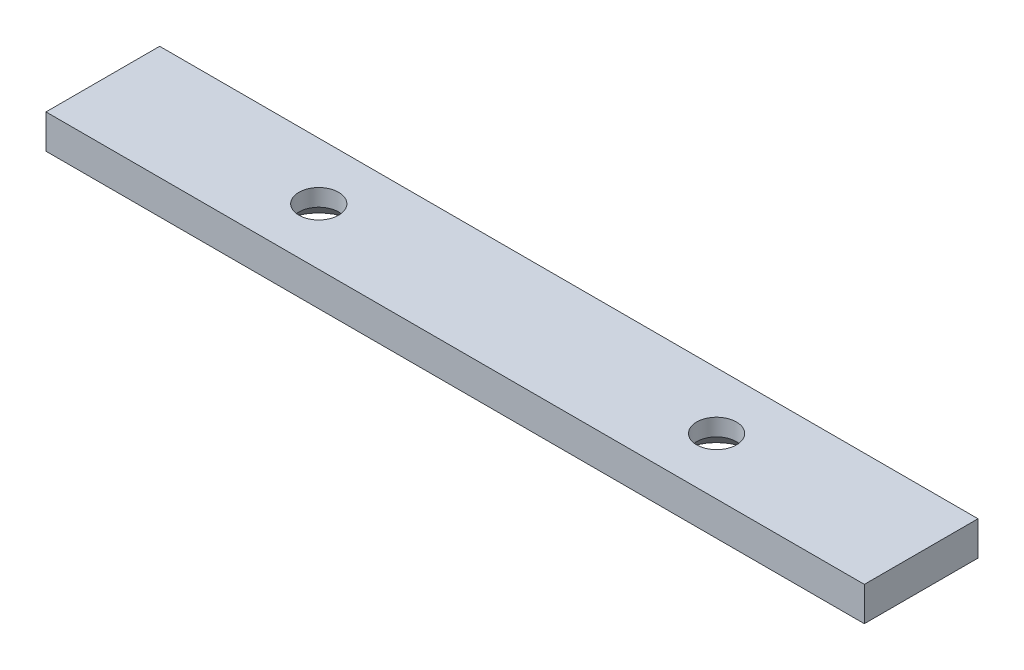
SolidWorks part; units mm, degrees
material "AISI 1020"
ref_plane "Front Plane" through (0, 0, 0) normal (0, 0, 1) x (1, 0, 0)
ref_plane "Top Plane" through (0, 0, 0) normal (0, 1, 0) x (1, 0, 0)
ref_plane "Right Plane" through (0, 0, 0) normal (1, 0, 0) x (0, 0, -1)
sketch "Sketch1" plane through (0, 0, 0) normal (0, 1, 0) x (1, 0, 0)
  line L1 (-72, 10) -> (72, 10)
  line L2 (-72, 10) -> (-72, -10)
  line L3 (-72, -10) -> (72, -10)
  line L4 (72, 10) -> (72, -10)
  line L5 (-72, 10) -> (72, -10) construction
  line L6 (-72, -10) -> (72, 10) construction
  point P0 (0, 0)
  dimension "D1" = 20
  dimension "D2" = 144
extrude "Boss-Extrude1" add sketch "Sketch1" along normal blind 6 contours L3 L4 L1 L2
hole_wizard "CSK for M2 Flat Head Machine Screw1" positions "Sketch4" profile "Sketch5" countersink size "M2" standard "ANSI Metric" end condition up to next
sketch "Sketch4" plane through (0, 0, 0) normal (0, -1, 0) x (-1, 0, 0)
  line L0 (72, 10) -> (72, -10) construction
  line L1 (72, 10) -> (-72, 10) construction
  point P0 (34, 0)
  dimension "D1" = 38
  dimension "D2" = 10
sketch "Sketch5" plane through (-34, 0, 0) normal (1, 0, 0) x (0, 0, -1)
  line L0 (0, 0) -> (0, 6)
  line L1 (0, 6) -> (3.5, 6)
  line L2 (3.5, 6) -> (3.5, 3)
  line L3 (3.5, 3) -> (6.5, 0)
  line L5 (6.5, 0) -> (0, 0)
  line L6 (-3.5, 3) -> (-6.5, 0) construction
  line L11 (0, -6.35) -> (0, 107.95) construction
  dimension "Thru Hole Dia." = 7
  dimension "Thru Hole Depth" = 6
  dimension "Near C'Sink Dia." = 13
  dimension "Near C'Sink Angle" = 90
pattern_linear "LPattern1" count 2 spacing 70 along (1, 0, 0) of "CSK for M2 Flat Head Machine Screw1"
